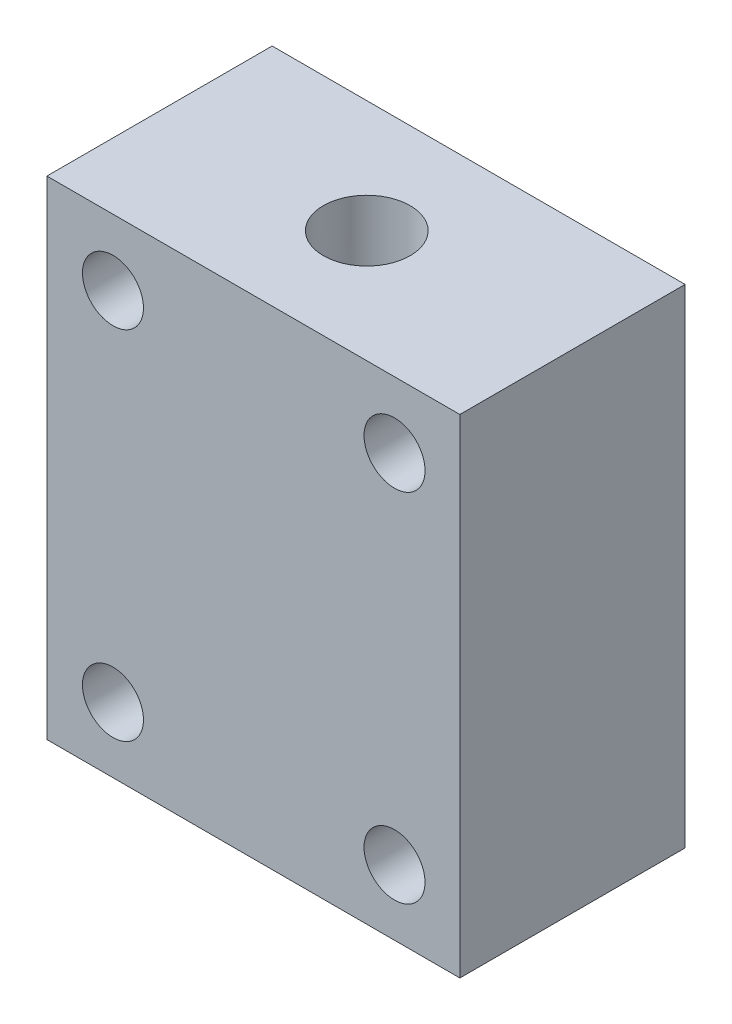
SolidWorks part; units mm, degrees
ref_plane "Front Plane" through (0, 0, 0) normal (1, 0, 0) x (0, 1, 0)
ref_plane "Top Plane" through (0, 0, 0) normal (0, 0, 1) x (0, 1, 0)
ref_plane "Right Plane" through (0, 0, 0) normal (0, 1, 0) x (-1, 0, 0)
sketch "Sketch1" plane through (0, 0, 0) normal (0, 0, 1) x (0, 1, 0)
  line L1 (-41.275, -34.925) -> (41.275, -34.925)
  line L2 (-41.275, -34.925) -> (-41.275, 34.925)
  line L3 (-41.275, 34.925) -> (41.275, 34.925)
  line L4 (41.275, -34.925) -> (41.275, 34.925)
  line L5 (-41.275, -34.925) -> (41.275, 34.925) construction
  line L6 (-41.275, 34.925) -> (41.275, -34.925) construction
  point P0 (0, 0)
extrude "Boss-Extrude1" add sketch "Sketch1" along normal mid plane 38.1
hole_wizard "3/8 Clearance Hole1" positions "Sketch3" profile "Sketch2" hole size "3/8" standard "ANSI Inch"
sketch "Sketch3" plane through (0, 0, -19.05) normal (0, 0, -1) x (-1, 0, 0)
  line L0 (-23.876, -30.226) -> (23.749, -30.226) construction
  line L1 (23.749, -30.226) -> (23.749, 30.099) construction
  line L2 (23.749, 30.099) -> (-23.876, 30.099) construction
  line L3 (-23.876, 30.099) -> (-23.876, -30.226) construction
  point P0 (-23.876, -30.226)
  point P1 (-23.876, 30.099)
  point P3 (23.749, -30.226)
  point P5 (23.749, 30.099)
sketch "Sketch2" plane through (23.876, -30.226, -19.05) normal (1, 0, 0) x (0, 1, 0)
  line L0 (0, 0) -> (0, 41.2001)
  line L1 (0, 41.2001) -> (5.1594, 38.1)
  line L2 (5.1594, 38.1) -> (5.1594, 0)
  line L5 (5.1594, 0) -> (0, 0)
  line L10 (0, 41.2001) -> (-5.1594, 38.1) construction
  line L11 (0, -6.35) -> (0, 107.95) construction
  dimension "Hole Dia." = 10.3187
  dimension "Hole Depth" = 38.1
  dimension "Drill Angle" = 118
sketch "Sketch4" plane through (0, 0, 0) normal (0, 0, 1) x (0, 1, 0)
  circle A0 centre (-17.653, -0.127) radius 7.3422
  circle A1 centre (17.399, -0.127) radius 7.3422
extrude "Cut-Extrude2" cut sketch "Sketch4" along normal blind 28.448 from offset 19.05
sketch "Sketch5" plane through (0, 0, 0) normal (0, 0, 1) x (0, 1, 0)
  circle A0 centre (-17.653, -0.127) radius 12.7254
  circle A1 centre (17.399, -0.127) radius 12.7254
extrude "Cut-Extrude4" cut sketch "Sketch5" along normal blind 2.8194 from offset 19.05
sketch "Sketch6" plane through (0, 0, 0) normal (0, 1, 0) x (-1, 0, 0)
  circle A0 centre (-0.127, 0) radius 7.3422
extrude "Cut-Extrude6" cut sketch "Sketch6" against normal blind 60.452 from offset 41.275
